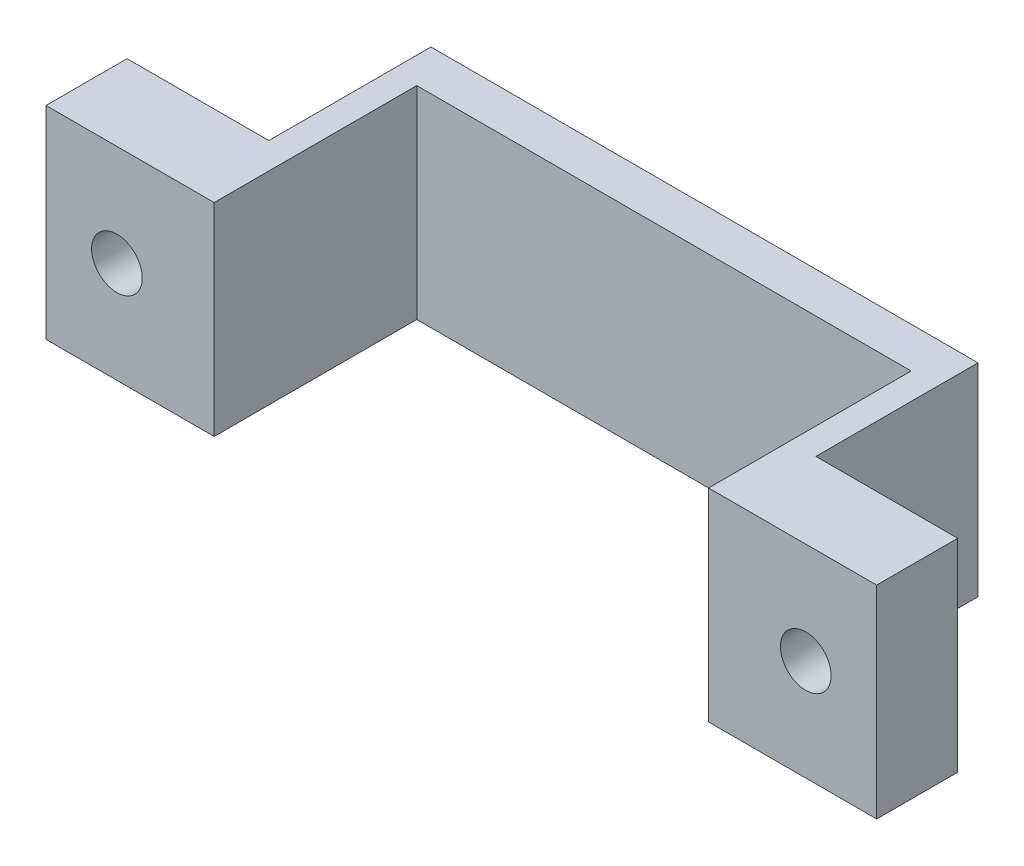
SolidWorks part; units mm, degrees
ref_plane "Спереди" through (0, 0, 0) normal (0, 0, 1) x (1, 0, 0)
ref_plane "Сверху" through (0, 0, 0) normal (0, 1, 0) x (1, 0, 0)
ref_plane "Справа" through (0, 0, 0) normal (1, 0, 0) x (0, 0, -1)
sketch "Эскиз1" plane through (0, 0, 0) normal (0, 1, 0) x (1, 0, 0)
  line L0 (-13.5, 2) -> (13.5, 2)
  line L1 (13.5, 2) -> (13.5, -6)
  line L2 (-13.5, 2) -> (-13.5, -6)
  line L3 (13.5, -6) -> (20.5, -6)
  line L4 (-13.5, -6) -> (-20.5, -6)
  line L5 (20.5, -6) -> (20.5, -10)
  line L6 (-20.5, -6) -> (-20.5, -10)
  line L7 (-20.5, -10) -> (-12.2, -10)
  line L8 (20.5, -10) -> (12.2, -10)
  line L9 (12.2, -10) -> (12.2, 0)
  line L10 (-12.2, -10) -> (-12.2, 0)
  line L11 (-12.2, 0) -> (12.2, 0)
  line L12 (16.35, -7.2854) -> (16.35, -8.9156) construction
  line L13 (-16.35, -7.2854) -> (-16.35, -9.2854) construction
  point P12 (0, 0)
  dimension "D1" = 27
  dimension "D2" = 8
  dimension "D3" = 8
  dimension "D4" = 7
  dimension "D5" = 7
  dimension "D6" = 4
  dimension "D7" = 4
  dimension "D8" = 8.3
  dimension "D9" = 8.3
  dimension "D10" = 2
  dimension "D11" = 4.15
  dimension "D12" = 2
  dimension "D13" = 4.15
  dimension "D14" = 32.7
extrude "Бобышка-Вытянуть1" add sketch "Эскиз1" along normal blind 10
ref_plane "Плоскость1" through (0, 0, 0) normal (-1, 0, 0) x (0, 0, 1)
sketch "Эскиз3" plane through (0, 0, 6) normal (0, 0, -1) x (-1, 0, 0)
  line L0 (20.5, 5) -> (-20.5, 5) construction
  line L1 (20.5, 10) -> (20.5, 0) construction
  line L2 (-20.5, 10) -> (-20.5, 0) construction
  line L3 (17, 10) -> (17, 0) construction
  line L4 (13.5, 10) -> (20.5, 10) construction
  line L5 (13.5, 0) -> (20.5, 0) construction
  circle A0 centre (17, 5) radius 1.25
  point P8 (0, 0)
  dimension "D1" = 2.5
extrude "Вырез-Вытянуть2" cut sketch "Эскиз3" against normal blind 4
mirror "Зеркальное отражение1" about plane through (0, 0, 0) normal (-1, 0, 0) of "Вырез-Вытянуть2"
